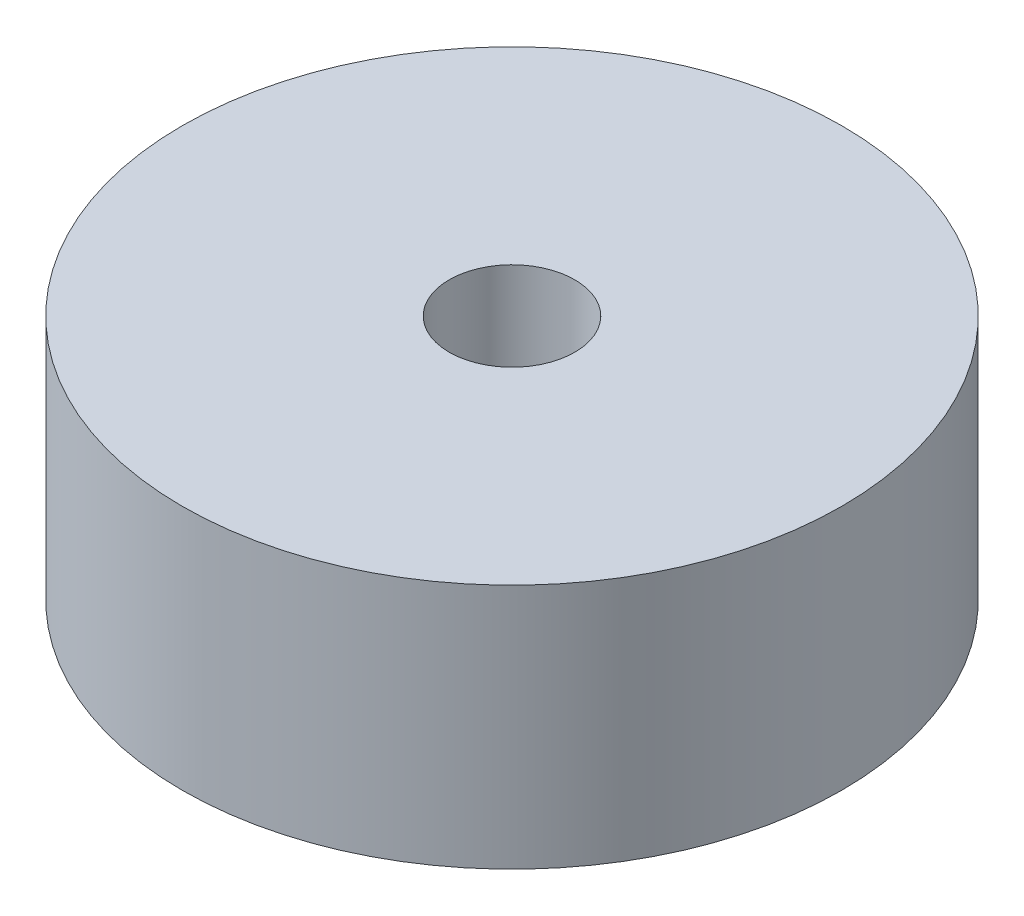
SolidWorks part; units mm, degrees
material "PF"
ref_plane "Front Plane" through (0, 0, 0) normal (0, 0, 1) x (1, 0, 0)
ref_plane "Top Plane" through (0, 0, 0) normal (0, 1, 0) x (1, 0, 0)
ref_plane "Right Plane" through (0, 0, 0) normal (1, 0, 0) x (0, 0, -1)
sketch "Sketch1" plane through (0, 0, 0) normal (0, 1, 0) x (1, 0, 0)
  circle A0 centre (0, 0) radius 31.5
  dimension "D1" = 63
extrude "Boss-Extrude1" add sketch "Sketch1" along normal blind 23.5
sketch "Sketch2" plane through (0, 23.5, 0) normal (0, 1, 0) x (1, 0, 0)
  circle A0 centre (0, 0) radius 6
  dimension "D1" = 12
extrude "Cut-Extrude1" cut sketch "Sketch2" against normal blind 23.5
